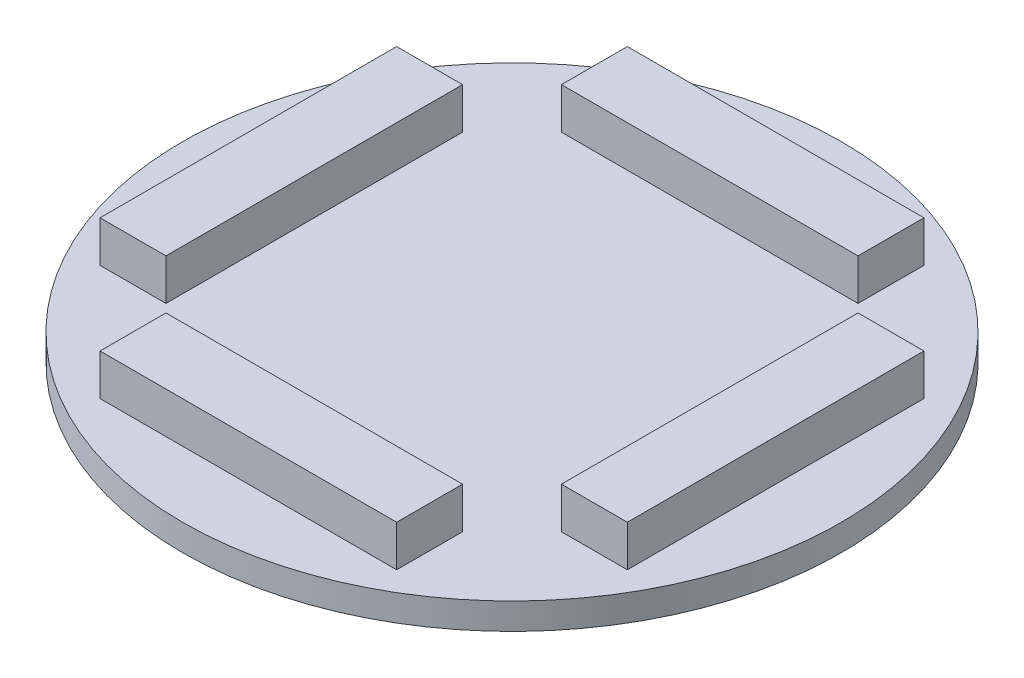
SolidWorks part; units mm, degrees
material "A-Glass Fiber"
ref_plane "Front Plane" through (0, 0, 0) normal (0, 0, 1) x (1, 0, 0)
ref_plane "Top Plane" through (0, 0, 0) normal (0, 1, 0) x (1, 0, 0)
ref_plane "Right Plane" through (0, 0, 0) normal (1, 0, 0) x (0, 0, -1)
sketch "Sketch1" plane through (0, 0, 0) normal (0, 1, 0) x (1, 0, 0)
  circle A0 centre (0, 0) radius 20
  dimension "D1" = 40
extrude "PCB" add sketch "Sketch1" along normal blind 1.6
sketch "Sketch2" plane through (0, 1.6, 0) normal (0, 1, 0) x (1, 0, 0)
  line L0 (0, 20) -> (0, 0) construction
  line L1 (-9, 16) -> (9, 16)
  line L2 (-9, 16) -> (-9, 12)
  line L3 (-9, 12) -> (9, 12)
  line L4 (9, 16) -> (9, 12)
  circle A0 centre (0, 0) radius 20 construction
  point P9 (0, 16)
  dimension "D1" = 4
  dimension "D2" = 18
  dimension "D3" = 16
extrude "Hirose Connector Stack" add sketch "Sketch2" along normal blind 2.5 contours L1 L4 L3 L2
pattern_circular "CirPattern1" count 4 over 360 about axis through (0, 0, 0) along (0, 1, 0) of "Hirose Connector Stack"
